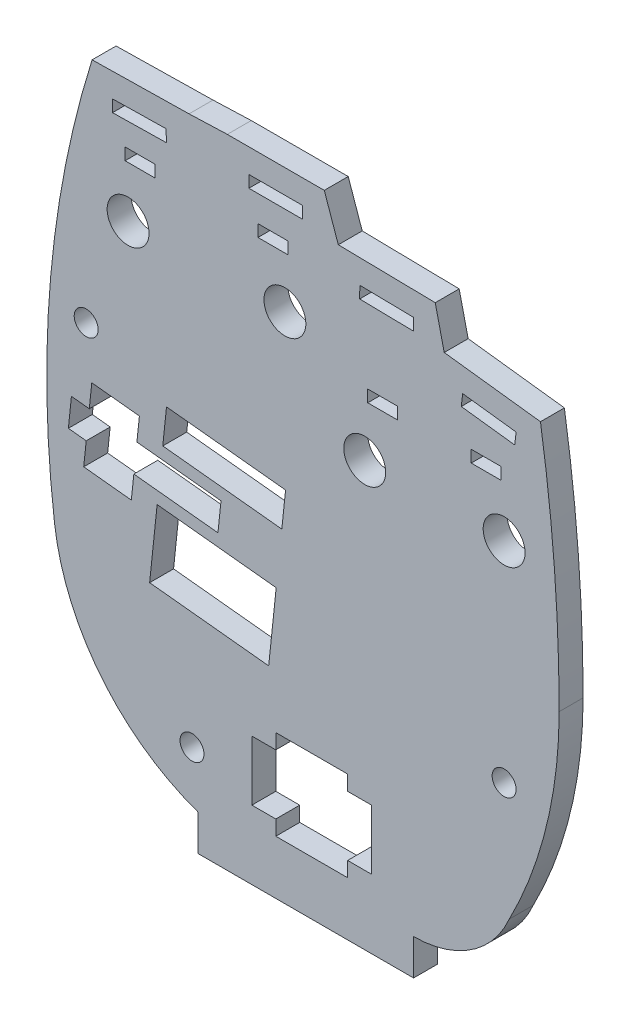
SolidWorks part; units mm, degrees
ref_plane "Front Plane" through (0, 0, 0) normal (0, 0, 1) x (1, 0, 0)
ref_plane "Top Plane" through (0, 0, 0) normal (0, 1, 0) x (1, 0, 0)
ref_plane "Right Plane" through (0, 0, 0) normal (1, 0, 0) x (0, 0, -1)
sketch "Sketch1" plane through (0, 0, 0) normal (0, 0, 1) x (1, 0, 0)
  line L0 (-4.5, 78.51) -> (-4.5, 76.51)
  line L1 (4.5, 78.51) -> (-4.5, 78.51)
  line L2 (-4.5, 76.51) -> (4.5, 76.51)
  line L3 (4.5, 76.51) -> (4.5, 78.51)
  line L4 (-4, -2.5) -> (0, -2.5)
  line L5 (0, 0) -> (18.54, 0) construction
  line L6 (0, 0) -> (0, 82.51) construction
  line L7 (12, 0) -> (0, 0)
  line L8 (0, 0) -> (-22.59, 0) construction
  line L9 (32.6473, 57.3216) -> (37.6473, 57.3216)
  line L10 (-12.9786, -18) -> (-12.9786, -24)
  line L11 (32.6473, 55.3216) -> (37.6473, 55.3216)
  line L12 (37.6473, 55.3216) -> (37.6473, 57.3216)
  line L13 (32.6473, 57.3216) -> (32.6473, 55.3216)
  line L14 (-27.3181, 78.0574) -> (-18.3194, 78.2135)
  line L15 (-27.3181, 78.0574) -> (-27.2834, 76.0577)
  line L16 (-27.2834, 76.0577) -> (-18.2848, 76.2138)
  line L17 (-18.2848, 76.2138) -> (-18.3194, 78.2135)
  line L18 (15.3631, 57.3998) -> (20.3631, 57.3998)
  line L19 (15.3631, 55.3998) -> (20.3631, 55.3998)
  line L20 (20.3631, 55.3998) -> (20.3631, 57.3998)
  line L21 (15.3631, 57.3998) -> (15.3631, 55.3998)
  line L22 (-2.9786, 72.1512) -> (2.0214, 72.1512)
  line L23 (14.0416, 71.7429) -> (14.0067, 69.7432)
  line L24 (14.0067, 69.7432) -> (23.0053, 69.5861)
  line L25 (-2.9786, 70.1512) -> (2.0214, 70.1512)
  line L26 (23.0402, 71.5858) -> (14.0416, 71.7429)
  line L27 (23.0053, 69.5861) -> (23.0402, 71.5858)
  line L28 (-22.59, 0) -> (-22.59, 82.14) construction
  line L29 (2.0214, 70.1512) -> (2.0214, 72.1512)
  line L30 (28.1404, 69.0671) -> (44.2196, 67.0929)
  line L31 (-2.9786, 72.1512) -> (-2.9786, 70.1512)
  line L32 (40.159, 63.5614) -> (31.2261, 64.6582)
  line L33 (1.6326, 35.9121) -> (1.0057, 29.9449)
  line L34 (31.2261, 64.6582) -> (30.9823, 62.6731)
  line L35 (-25.179, 72.1512) -> (-20.179, 72.1512)
  line L36 (18.54, 0) -> (18.54, 75.665) construction
  line L37 (0, 0) -> (36.18, 0) construction
  line L38 (-25.179, 70.1512) -> (-20.179, 70.1512)
  line L39 (30.9823, 62.6731) -> (39.9152, 61.5763)
  line L40 (-20.179, 70.1512) -> (-20.179, 72.1512)
  line L41 (-25.179, 72.1512) -> (-25.179, 70.1512)
  line L42 (39.9152, 61.5763) -> (40.159, 63.5614)
  line L43 (1.6326, 35.9121) -> (-18.2579, 38.0017)
  line L44 (0.0654, 20.9942) -> (-1.1883, 9.0599)
  line L45 (12, 0) -> (12, -2.5)
  line L46 (-18.8848, 32.0346) -> (1.0057, 29.9449)
  line L47 (12, -15) -> (0, -15)
  line L48 (-9.666, 24.0728) -> (-9.153, 28.9559)
  line L49 (-34.657, 26.6982) -> (-34.144, 31.5814)
  line L50 (-9.153, 28.9559) -> (-23.2057, 30.4322)
  line L51 (-32.0928, 22.4068) -> (-31.6749, 26.385)
  line L52 (-34.657, 26.6982) -> (-31.6749, 26.385)
  line L53 (-23.7187, 25.5491) -> (-9.666, 24.0728)
  line L54 (-23.2057, 30.4322) -> (-22.7877, 34.4103)
  line L55 (-24.1366, 21.571) -> (-32.0928, 22.4068)
  line L56 (-18.8848, 32.0346) -> (-18.2579, 38.0017)
  line L57 (-30.744, 35.2462) -> (-31.1619, 31.2681)
  line L58 (-22.7877, 34.4103) -> (-30.744, 35.2462)
  line L59 (-31.1619, 31.2681) -> (-34.144, 31.5814)
  line L60 (-24.1366, 21.571) -> (-23.7187, 25.5491)
  line L61 (-19.8251, 23.0838) -> (0.0654, 20.9942)
  line L62 (-21.0789, 11.1495) -> (-1.1883, 9.0599)
  line L63 (0, -15) -> (0, -12.5)
  line L64 (-4, -12.5) -> (-4, -2.5)
  line L65 (-19.8251, 23.0838) -> (-21.0789, 11.1495)
  line L66 (-12.9786, -24) -> (23.0214, -24)
  line L67 (-4, -12.5) -> (0, -12.5)
  line L68 (0, -2.5) -> (0, 0)
  line L69 (16, -12.5) -> (12, -12.5)
  line L70 (16, -12.5) -> (16, -2.5)
  line L71 (16, -2.5) -> (12, -2.5)
  line L72 (12, -12.5) -> (12, -15)
  line L73 (23.0214, -24) -> (23.0214, -18)
  line L74 (36.18, 0) -> (36.18, 68.08) construction
  line L75 (10.4412, 75.8064) -> (26.6388, 75.5236)
  line L76 (-8.1, 82.51) -> (8.1, 82.51)
  line L77 (-14.4912, 82.2805) -> (-30.6888, 81.9995)
  line L78 (28.1404, 69.0671) -> (26.6388, 75.5236)
  line L79 (-9.4095, 26.5144) -> (4.399, 25.0637) construction
  line L80 (39, -7.5) -> (16, -7.5) construction
  line L81 (10.4412, 75.8064) -> (8.1, 82.51)
  line L82 (-8.1, 82.51) -> (-14.4912, 82.2805)
  line L83 (-34.657, 26.6982) -> (47.343, 26.6982) construction
  line L84 (35.6925, 64.1098) -> (36.18, 68.08) construction
  line L85 (38.1473, 11.8216) -> (-36.9684, 11.8216) construction
  line L86 (-18.8848, 32.0346) -> (-19.8251, 23.0838) construction
  line L87 (-19.355, 27.5592) -> (-38.241, 29.5433) construction
  arc A0 (23.0214, -18) -> (39, -7.5) centre (23.0214, -0.592) ccw
  circle A1 centre (38.1473, 11.8216) radius 2
  arc A2 (-36.9684, 11.8216) -> (-30.6888, 81.9995) centre (127.1005, 32.5105) cw
  circle A3 centre (-24.679, 61.6512) radius 3.5
  circle A4 centre (1.5214, 61.6512) radius 3.5
  circle A5 centre (14.8631, 46.8216) radius 3.5
  circle A6 centre (38.1473, 46.8216) radius 3.5
  arc A7 (-36.9684, 11.8216) -> (-12.9786, -18) centre (-0.7625, 16.3871) ccw
  circle A8 centre (-31.6815, 43.4564) radius 2
  circle A9 centre (-14, -9.1244) radius 2
  arc A10 (47.343, 26.6982) -> (39, -7.5) centre (-26.9181, 26.6982) cw
  arc A11 (47.343, 26.6982) -> (44.2196, 67.0929) centre (-215.4276, 26.6982) ccw
  dimension "D1" = 7
  dimension "D15" = 22.59
  dimension "D16" = 82.14
  dimension "D21" = 18
  dimension "D22" = 14.8631
  dimension "D23" = 68.08
  dimension "D24" = 4
  dimension "D27" = 5
  dimension "D28" = 23.0214
  dimension "D29" = 55.3216
  dimension "D30" = 32.6473
  dimension "D39" = 25.179
  dimension "D40" = 9.153
  dimension "D41" = 9.666
  dimension "D42" = 12.9786
  dimension "D43" = 14
  dimension "D44" = 4
  dimension "D47" = 57.3216
  dimension "D48" = 4
  dimension "D65" = 61.6512
  dimension "D72" = 9.1244
  dimension "D61" = 46.8216
  dimension "D62" = 2
  dimension "D53" = 9
  dimension "D2" = 4
  dimension "D8" = 12
  dimension "D14" = 10
  dimension "D9" = 9
  dimension "D10" = 1.0057
  dimension "D11" = 1.5214
  dimension "D12" = 6
  dimension "D13" = 82.51
  dimension "D17" = 18.54
  dimension "D18" = 2.5
  dimension "D19" = 75.665
  dimension "D20" = 36.18
  dimension "D26" = 16.2
  dimension "D31" = 55.3998
  dimension "D32" = 15.3631
  dimension "D33" = 70.1512
  dimension "D35" = 38.1473
  dimension "D36" = 2.9786
  dimension "D37" = 4
  dimension "D38" = 4.91
  dimension "D45" = 20
  dimension "D46" = 4
  dimension "D49" = 4.5
  dimension "D50" = 24.679
  dimension "D51" = 25.1285
  dimension "D52" = 31.6815
  dimension "D54" = 8
  dimension "D56" = 14.13
  dimension "D57" = 72.1512
  dimension "D58" = 11.8216
  dimension "D59" = 21.571
  dimension "D60" = 43.4564
  dimension "ThumbLinkLengthMCP" = 18.99
extrude "Boss-Extrude1" add sketch "Sketch1" along normal blind 4
equation "\"D13@Sketch1\"= \"HL@parametersSketch@prostheticParameters.SLDPRT\" * 0.446'Middle Base Frame"
equation "\"D15@Sketch1\"= \"HB@parametersSketch@prostheticParameters.SLDPRT\" * 0.251'Index Base Frame X"
equation "\"D16@Sketch1\"= \"HL@parametersSketch@prostheticParameters.SLDPRT\" * 0.444'Index Base Frame Y"
equation "\"D17@Sketch1\"= \"HB@parametersSketch@prostheticParameters.SLDPRT\" * 0.206'Ring Base Frame X"
equation "\"D19@Sketch1\"= \"HL@parametersSketch@prostheticParameters.SLDPRT\" * 0.409'Ring base Frame Y"
equation "\"D20@Sketch1\"= \"HB@parametersSketch@prostheticParameters.SLDPRT\" * 0.402'Pinky Base Frame X"
equation "\"D23@Sketch1\"= \"HL@parametersSketch@prostheticParameters.SLDPRT\" * 0.368'Pinky Base Frame Y"
equation "\"D26@Sketch1\"= \"fingerWidth@parametersSketch@prostheticParameters.SLDPRT\"'Fingers Width"
equation "\"D59@Sketch1\"= \"HL@parametersSketch@prostheticParameters.SLDPRT\" * 0.1166'Hole Thumb Y"
equation "\"D40@Sketch1\"= \"HB@parametersSketch@prostheticParameters.SLDPRT\" * 0.1017'Hole Thumb X1"
equation "\"D41@Sketch1\"= \"HB@parametersSketch@prostheticParameters.SLDPRT\" * 0.1074'Hole Thumb X2"
equation "\"ThumbLinkLengthMCP@Sketch1\"= \"HB@parametersSketch@prostheticParameters.SLDPRT\" * 0.211"
